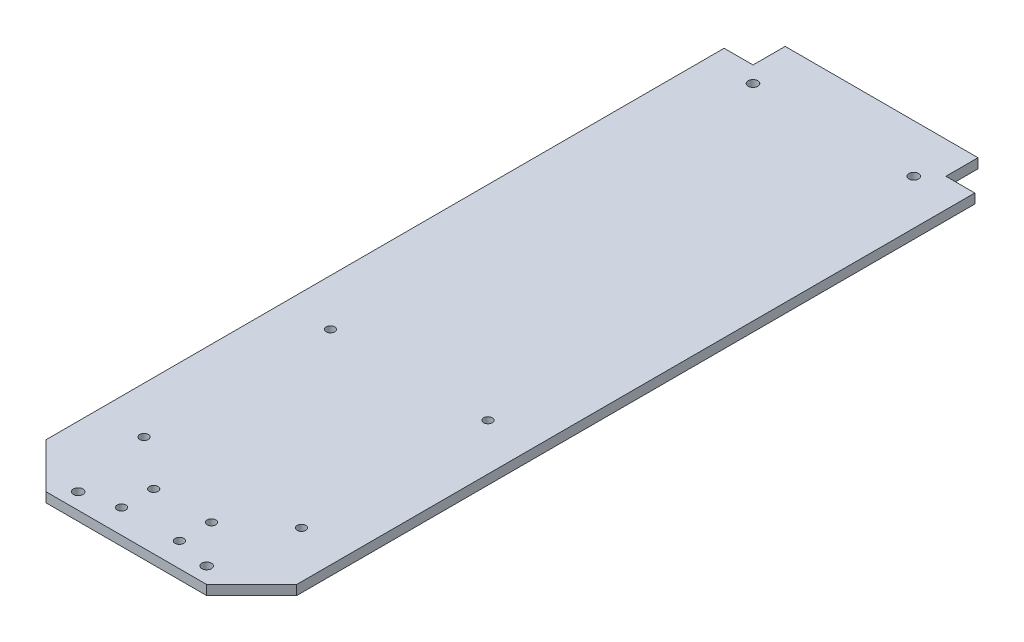
SolidWorks part; units mm, degrees
ref_plane "Front Plane" through (0, 0, 0) normal (0, 0, 1) x (1, 0, 0)
ref_plane "Top Plane" through (0, 0, 0) normal (0, 1, 0) x (1, 0, 0)
ref_plane "Right Plane" through (0, 0, 0) normal (1, 0, 0) x (0, 0, -1)
sketch "Sketch1" plane through (0, 0, 0) normal (0, 1, 0) x (1, 0, 0)
  line L0 (19.1206, 112.5) -> (28.1206, 112.5)
  line L1 (-49.8794, 112.5) -> (-40.8794, 112.5)
  line L2 (-49.8794, 112.5) -> (-49.8794, -112.5)
  line L3 (-49.8794, -112.5) -> (28.1206, -112.5)
  line L4 (28.1206, 112.5) -> (28.1206, -112.5)
  line L8 (-40.8794, 112.5) -> (-40.8794, 122.5)
  line L9 (-40.8794, 122.5) -> (19.1206, 122.5)
  line L10 (19.1206, 112.5) -> (19.1206, 122.5)
  dimension "D1" = 225
  dimension "D2" = 78
  dimension "D3" = 10
  dimension "D4" = 60
  dimension "D5" = 9
extrude "Boss-Extrude1" add sketch "Sketch1" along normal blind 3
sketch "Sketch2" plane through (0, 3, 0) normal (0, 1, 0) x (1, 0, 0)
  line L2 (-49.8794, 112.5) -> (-49.8794, -112.5) construction
  line L3 (28.1206, 112.5) -> (19.1206, 112.5) construction
  line L4 (28.1206, -112.5) -> (28.1206, 112.5) construction
  line L5 (-49.8794, -112.5) -> (28.1206, -112.5) construction
  line L7 (-40.8794, 122.5) -> (-40.8794, 112.5) construction
  line L8 (-40.8794, 112.5) -> (-49.8794, 112.5) construction
  line L9 (19.1206, 112.5) -> (19.1206, 122.5) construction
  circle A0 centre (14.1206, 107.5) radius 1.5
  circle A1 centre (-35.8794, 107.5) radius 1.5
  circle A2 centre (-30.8794, -107.5) radius 1.5
  circle A3 centre (9.1206, -107.5) radius 1.5
  circle A4 centre (-35.3794, -82.5) radius 1.35
  circle A5 centre (13.6206, -82.5) radius 1.35
  circle A6 centre (-35.3794, -24.5) radius 1.35
  circle A7 centre (13.6206, -24.5) radius 1.35
  circle A8 centre (-19.8794, -105) radius 1.35
  circle A9 centre (-1.8794, -105) radius 1.35
  circle A10 centre (-19.8794, -95) radius 1.35
  circle A11 centre (-1.8794, -95) radius 1.35
  dimension "D5" = 3
  dimension "D6" = 3
  dimension "D7" = 3
  dimension "D8" = 3
  dimension "D14" = 2.7
  dimension "D15" = 2.7
  dimension "D19" = 2.7
  dimension "D20" = 2.7
  dimension "D28" = 2.7
  dimension "D29" = 2.7
  dimension "D30" = 2.7
  dimension "D31" = 2.7
  dimension "D2" = 5
  dimension "D3" = 5
  dimension "D4" = 5
  dimension "D9" = 19
  dimension "D10" = 5
  dimension "D11" = 5
  dimension "D12" = 19
  dimension "D13" = 5
  dimension "D16" = 49
  dimension "D17" = 30
  dimension "D18" = 14.5
  dimension "D21" = 49
  dimension "D22" = 58
  dimension "D23" = 14.5
  dimension "D24" = 7.5
  dimension "D25" = 10
  dimension "D26" = 18
  dimension "D27" = 18
  dimension "D32" = 30
extrude "Cut-Extrude1" cut sketch "Sketch2" against normal blind 25
chamfer "Chamfer1" distance 14 angle 45 2 edges at (-49.8794, 1.5, 112.5) (28.1206, 1.5, 112.5)
